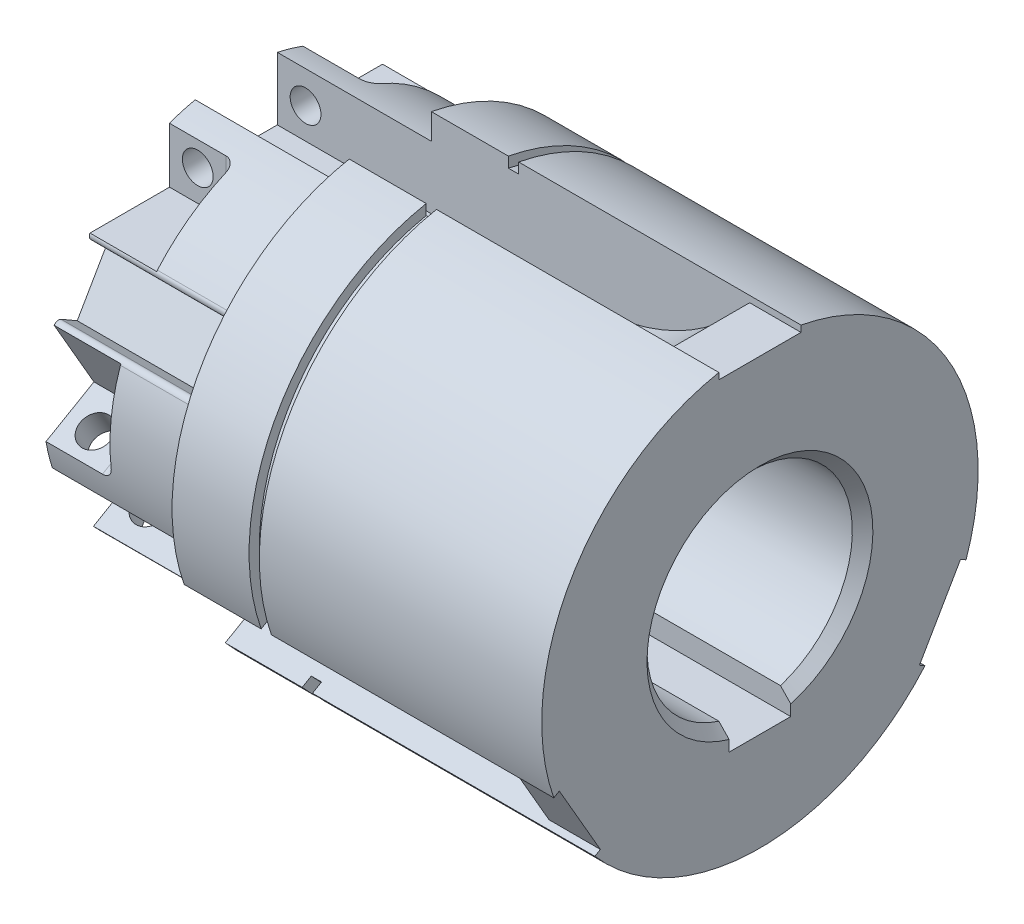
SolidWorks part; units mm, degrees
material "1.0060 (E335)"
ref_plane "Front Plane" through (0, 0, 0) normal (0, 0, 1) x (1, 0, 0)
ref_plane "Top Plane" through (0, 0, 0) normal (0, 1, 0) x (1, 0, 0)
ref_plane "Right Plane" through (0, 0, 0) normal (1, 0, 0) x (0, 0, -1)
sketch "Sketch1" plane through (0, 0, 0) normal (0, 0, 1) x (1, 0, 0)
  line L0 (-534.701, 0) -> (26200.3507, 0) construction
  line L1 (0, 20) -> (0, 42.5)
  line L2 (0, 20) -> (-102, 20)
  line L3 (0, 42.5) -> (-55, 42.5)
  line L4 (-55, 42.5) -> (-55, 40.5)
  line L5 (-55, 40.5) -> (-57, 40.5)
  line L6 (-57, 40.5) -> (-57, 42.5)
  line L7 (-57, 42.5) -> (-72, 42.5)
  line L8 (-72, 42.5) -> (-72, 37.6)
  line L9 (-72, 37.6) -> (-102, 37.6)
  line L10 (-102, 37.6) -> (-102, 20)
  dimension "D1" = 40
  dimension "D2" = 75.2
  dimension "D3" = 2
  dimension "D4" = 2
  dimension "D5" = 15
  dimension "D7" = 85
  dimension "D8" = 30
  dimension "D9" = 55
revolve "Revolve1" add sketch "Sketch1" angle 360 about L0
sketch "Sketch3" plane through (0, 0, 0) normal (0, 0, 1) x (1, 0, 0)
  line L0 (-102, 24.5) -> (-42, 24.5)
  line L1 (-102, 37.6) -> (-102, -37.6) construction
  line L2 (0, 42.5) -> (-55, 42.5) construction
  line L3 (0, 42.5) -> (-55, 42.5)
  line L4 (-57, -42.5) -> (-57, 42.5) construction
  line L5 (-55, 42.5) -> (-55, -42.5) construction
  line L6 (-57, 40.5) -> (-57, 42.5)
  line L7 (-55, 42.5) -> (-55, 40.5)
  line L8 (-55, 40.5) -> (-57, 40.5) construction
  line L9 (-55, 40.5) -> (-57, 40.5)
  line L10 (-72, 37.6) -> (-102, 37.6) construction
  line L11 (-72, 42.5) -> (-72, -42.5) construction
  line L12 (-57, 42.5) -> (-72, 42.5) construction
  line L13 (-72, 37.6) -> (-102, 37.6)
  line L14 (-72, 42.5) -> (-72, 37.6)
  line L15 (-57, 42.5) -> (-72, 42.5)
  line L16 (-102, 37.6) -> (-102, 24.5)
  line L17 (-10, 40.5) -> (0, 40.5)
  line L18 (0, -42.5) -> (0, 42.5) construction
  line L19 (0, 40.5) -> (0, 42.5)
  arc A0 (-42, 24.5) -> (-10, 40.5) centre (-42, 64.5) ccw
  dimension "D2" = 40
  dimension "D1" = 18
  dimension "D3" = 2
  dimension "D4" = 60
extrude "Cut-Extrude1" cut sketch "Sketch3" against normal mid plane 16
pattern_circular "CirPattern1" count 3 over 360 about axis through (0, 0, 0) along (1, 0, 0) of "Cut-Extrude1"
sketch "Sketch4" plane through (-102, 0, 0) normal (-1, 0, 0) x (0, 0, 1)
  line L0 (-13, 35.2812) -> (-13, 24.5)
  line L1 (-13, 24.5) -> (-28.5221, 24.5)
  line L2 (-8, 24.5) -> (8, 24.5) construction
  line L3 (0, -1000) -> (0, 49000) construction
  line L4 (-8, 24.5) -> (-8, 40.5) construction
  line L5 (13, 35.2812) -> (13, 24.5)
  line L6 (13, 24.5) -> (28.5221, 24.5)
  arc A0 (-8, 36.7391) -> (-35.817, -11.4413) centre (0, 0) ccw construction
  arc A1 (-8, 36.7391) -> (-35.817, -11.4413) centre (0, 0) ccw construction
  arc A2 (-13, 35.2812) -> (-28.5221, 24.5) centre (0, 0) ccw
  arc A3 (13, 35.2812) -> (28.5221, 24.5) centre (0, 0) cw
  dimension "D1" = 5
extrude "Cut-Extrude2" cut sketch "Sketch4" against normal blind 13
fillet "Fillet1" radius 2 2 edges at (-89, 29.8906, -13) (-89, 29.8906, 13)
sketch "Sketch6" plane through (0, 0, 13) normal (0, 0, 1) x (1, 0, 0)
  line L0 (-91, 24.5) -> (-102, 24.5) construction
  circle A0 centre (-96.5, 30.5) radius 3
  point P2 (-96.5, 24.5)
  dimension "D1" = 6
  dimension "D2" = 6
extrude "Cut-Extrude3" cut sketch "Sketch6" against normal up to surface (26 mm away) up to face at (-96.5, 29.8906, -13)
pattern_circular "CirPattern2" count 3 over 360 about axis through (0, 0, 0) along (1, 0, 0) of "Cut-Extrude2", "Fillet1", "Cut-Extrude3"
sketch "Sketch7" plane through (-102, 0, 0) normal (-1, 0, 0) x (0, 0, 1)
  line L0 (0, -1000) -> (0, 49000) construction
  line L1 (-6, -37.1182) -> (-6, -32.3)
  line L2 (-6, -32.3) -> (6, -32.3)
  line L3 (6, -32.3) -> (6, -37.1182)
  arc A0 (-27.817, -25.2977) -> (27.817, -25.2977) centre (0, 0) ccw construction
  arc A1 (-6.9566, -36.9509) -> (6.9566, -36.9509) centre (0, 0) ccw construction
  arc A2 (-6, -37.1182) -> (6, -37.1182) centre (0, 0) ccw
  point P8 (0, -32.3)
  dimension "D1" = 12
  dimension "D2" = 32.3
extrude "Cut-Extrude4" cut sketch "Sketch7" against normal up to surface (30 mm away) up to face at (-72, -33.299, 0)
fillet "Fillet2" radius 1 2 edges at (-87, -37.1182, 6) (-87, -37.1182, -6)
pattern_circular "CirPattern3" count 3 over 360 about axis through (0, 0, 0) along (1, 0, 0) of "Cut-Extrude4", "Fillet2"
ref_plane "Plane1" through (0, -23.3, 0) normal (0, 1, 0) x (1, 0, 0)
sketch "Sketch9" plane through (0, -23.3, 0) normal (0, 1, 0) x (1, 0, 0)
  line L0 (-102, 8) -> (-102, -8) construction
  line L1 (-102, -6) -> (0, -6)
  line L2 (-102, -6) -> (-102, 6)
  line L3 (-102, 6) -> (0, 6)
  line L4 (0, -6) -> (0, 6)
  line L5 (0, 8) -> (0, -8) construction
  point P8 (-102, 0)
  point P9 (0, 0)
  dimension "D1" = 12
extrude "Cut-Extrude5" cut sketch "Sketch9" along normal up to next
chamfer "Chamfer2" distance 2 angle 45 2 edges at (0, 20, 0) (-102, 20, 0)
